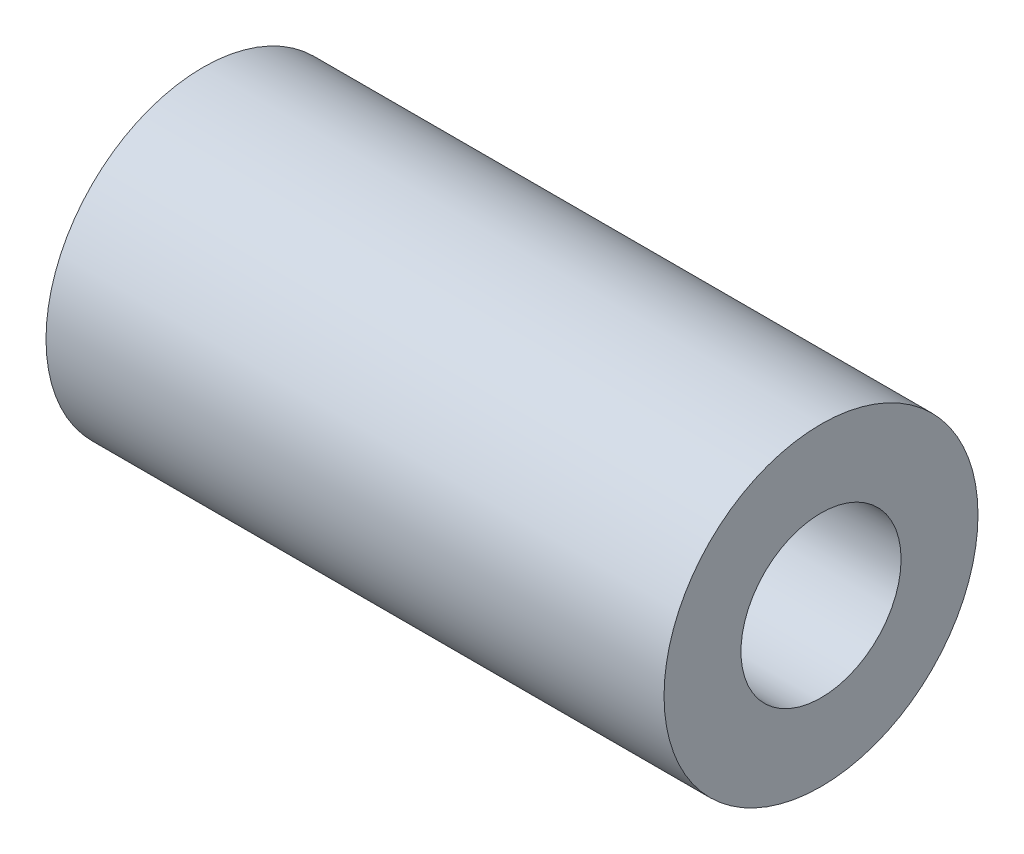
SolidWorks part; units mm, degrees
material "ABS"
ref_plane "Front Plane" through (0, 0, 0) normal (0, 0, 1) x (1, 0, 0)
ref_plane "Top Plane" through (0, 0, 0) normal (0, 1, 0) x (1, 0, 0)
ref_plane "Right Plane" through (0, 0, 0) normal (1, 0, 0) x (0, 0, -1)
sketch "Sketch1" plane through (0, 0, 0) normal (1, 0, 0) x (0, 0, -1)
  circle A0 centre (0, 0) radius 6.35
  circle A1 centre (0, 0) radius 3.2385
  dimension "D1" = 12.7
  dimension "D2" = 6.477
extrude "Boss-Extrude1" add sketch "Sketch1" along normal blind 25
